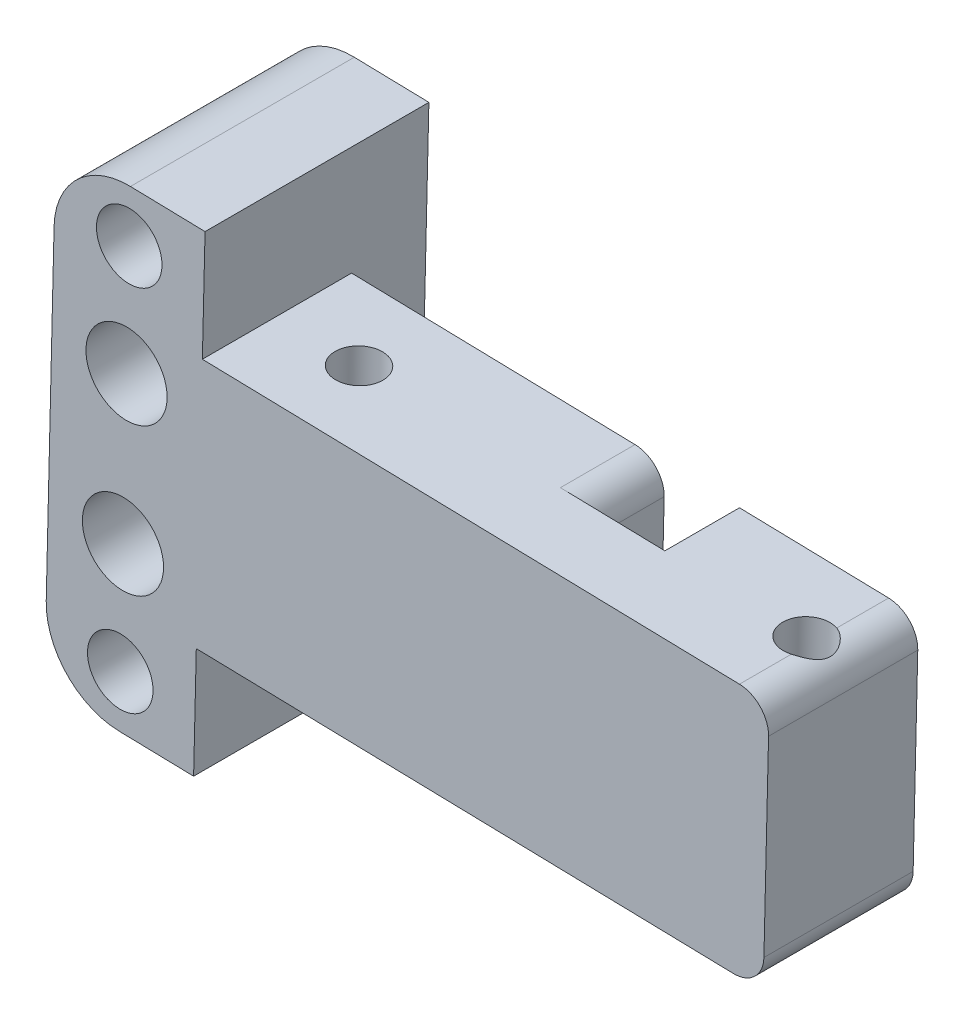
SolidWorks part; units mm, degrees
material "聚丁二烯(PB)"
ref_plane "前视基准面" through (0, 0, 0) normal (0, 0, 1) x (1, 0, 0)
ref_plane "上视基准面" through (0, 0, 0) normal (0, 1, 0) x (1, 0, 0)
ref_plane "右视基准面" through (0, 0, 0) normal (1, 0, 0) x (0, 0, -1)
other "Configuration Table"
sketch "草图1" plane through (0, 0, 0) normal (0, 0, 1) x (1, 0, 0)
  line L0 (24.1852, -7.0163) -> (24.4965, 5.98)
  line L1 (22.545, 8.0273) -> (-13.4447, 8.8895)
  line L2 (-13.4447, 8.8895) -> (-13.2651, 16.3873)
  line L3 (-13.2651, 16.3873) -> (-18.2636, 16.5071)
  line L4 (-23.3819, 11.6283) -> (-23.9088, -10.3654)
  line L5 (-19.03, -15.4837) -> (-14.0315, -15.6035)
  line L6 (-14.0315, -15.6035) -> (-13.8518, -8.1056)
  line L7 (-13.8518, -8.1056) -> (22.1378, -8.9678)
  arc A0 (24.4965, 5.98) -> (22.545, 8.0273) centre (22.4971, 6.0279) ccw
  arc A1 (-18.2636, 16.5071) -> (-23.3819, 11.6283) centre (-18.3834, 11.5085) ccw
  arc A2 (-23.9088, -10.3654) -> (-19.03, -15.4837) centre (-18.9103, -10.4852) ccw
  arc A3 (22.1378, -8.9678) -> (24.1852, -7.0163) centre (22.1857, -6.9684) ccw
  arc A4 (-16.7504, -12.0373) -> (-21.142, -11.9321) centre (-18.9462, -11.9847) ccw
  arc A5 (-21.142, -11.9321) -> (-16.7504, -12.0373) centre (-18.9462, -11.9847) ccw
  arc A6 (-16.0473, -4.552) -> (-21.4859, -4.4217) centre (-18.7666, -4.4869) ccw
  arc A7 (-21.4859, -4.4217) -> (-16.0473, -4.552) centre (-18.7666, -4.4869) ccw
  arc A8 (-15.8078, 5.4451) -> (-21.2464, 5.5754) centre (-18.5271, 5.5103) ccw
  arc A9 (-21.2464, 5.5754) -> (-15.8078, 5.4451) centre (-18.5271, 5.5103) ccw
  arc A10 (-16.1517, 12.9555) -> (-20.5432, 13.0607) centre (-18.3475, 13.0081) ccw
  arc A11 (-20.5432, 13.0607) -> (-16.1517, 12.9555) centre (-18.3475, 13.0081) ccw
extrude "凸台-拉伸1" add sketch "草图1" against normal blind 15
sketch "草图2" plane through (0, 0, -15) normal (0, 0, -1) x (-1, 0, 0)
  line L0 (13.4447, 8.8895) -> (13.8518, -8.1056)
  line L1 (13.8518, -8.1056) -> (-33.4158, -15.1213)
  line L2 (-33.4158, -15.1213) -> (-27.3795, 15.7432)
  line L3 (-27.3795, 15.7432) -> (13.4447, 8.8895)
extrude "切除-拉伸1" cut sketch "草图2" against normal blind 5
sketch "草图3" plane through (0.2051, 8.5625, 0) normal (0.024, 0.9997, 0) x (0.9997, -0.024, 0)
  line L0 (22.3463, 10) -> (-13.6537, 10) construction
  line L1 (12.3463, 10) -> (7.3463, 10)
  line L2 (12.3463, 10) -> (12.3463, 5)
  line L3 (12.3463, 5) -> (7.3463, 5)
  line L4 (7.3463, 10) -> (7.3463, 5)
  line L6 (24.3463, 10) -> (24.3463, 0) construction
  line L7 (22.3463, 0) -> (-13.6537, 0) construction
  circle A0 centre (21.8463, 5) radius 1.6
  circle A1 centre (-8.1537, 5) radius 1.6
  dimension "D3" = 2.5
  dimension "D4" = 3.2
  dimension "D1" = 5
  dimension "D2" = 12
  dimension "D6" = 5
  dimension "D5" = 2
extrude "切除-拉伸2" cut sketch "草图3" against normal blind 22
fillet "圆角1" radius 2 2 edges at (7.1421, -8.6086, -7.5) (7.5493, 8.3865, -7.5)
